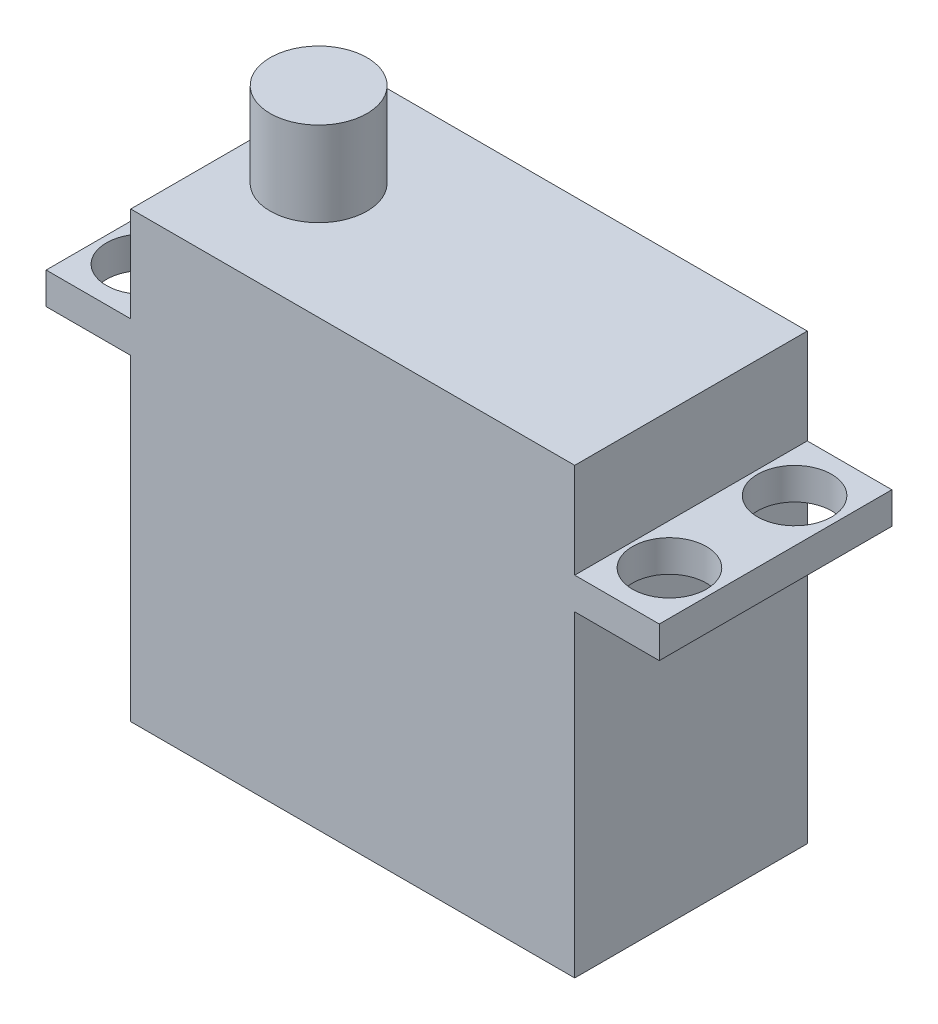
SolidWorks part; units mm, degrees
ref_plane "前视基准面" through (0, 0, 0) normal (0, 0, 1) x (1, 0, 0)
ref_plane "上视基准面" through (0, 0, 0) normal (0, 1, 0) x (1, 0, 0)
ref_plane "右视基准面" through (0, 0, 0) normal (1, 0, 0) x (0, 0, -1)
sketch "草图1" plane through (0, 0, 0) normal (0, 1, 0) x (1, 0, 0)
  line L1 (-21, 11) -> (21, 11)
  line L2 (-21, 11) -> (-21, -11)
  line L3 (-21, -11) -> (21, -11)
  line L4 (21, 11) -> (21, -11)
  line L5 (-21, 11) -> (21, -11) construction
  line L6 (-21, -11) -> (21, 11) construction
  point P0 (0, 0)
  dimension "D1" = 42
  dimension "D2" = 22
extrude "凸台-拉伸1" add sketch "草图1" along normal blind 42
ref_plane "基准面1" through (0, 30, 0) normal (0, 1, 0) x (1, 0, 0)
sketch "草图2" plane through (0, 30, 0) normal (0, 1, 0) x (1, 0, 0)
  line L0 (0, 0) -> (-26.2222, 0) construction
  line L1 (0, 13.4389) -> (0, -8.3961) construction
  line L2 (-29, -11) -> (-21, -11)
  line L3 (-29, -11) -> (-29, 11)
  line L4 (-29, 11) -> (-21, 11)
  line L5 (-21, -11) -> (-21, 11)
  line L6 (-29, -11) -> (-21, 11) construction
  line L7 (-29, 11) -> (-21, -11) construction
  line L8 (29, -11) -> (21, -11)
  line L9 (29, -11) -> (29, 11)
  line L10 (21, -11) -> (21, 11)
  line L11 (29, 11) -> (21, 11)
  point P3 (-25, 0)
  dimension "D1" = 8
extrude "凸台-拉伸2" add sketch "草图2" along normal blind 3
sketch "草图3" plane through (0, 33, 0) normal (0, 1, 0) x (1, 0, 0)
  line L0 (-36.7181, 0) -> (32.6031, 0) construction
  line L1 (0, 17.1245) -> (0, -17.2512)
  circle A0 centre (-24.8797, 5.9192) radius 3.5
  circle A1 centre (-24.8797, -5.9192) radius 3.5
  circle A2 centre (24.8797, -5.9192) radius 3.5
  circle A3 centre (24.8797, 5.9192) radius 3.5
  dimension "D1" = 7
extrude "切除-拉伸1" cut sketch "草图3" against normal blind 3 contours A1 | A0 | A3 | A2
sketch "草图4" plane through (0, 42, 0) normal (0, 1, 0) x (1, 0, 0)
  line L0 (-0.3798, 0) -> (-18.6756, 0) construction
  circle A0 centre (-14.224, 0) radius 4.5817
extrude "凸台-拉伸3" add sketch "草图4" along normal blind 8
